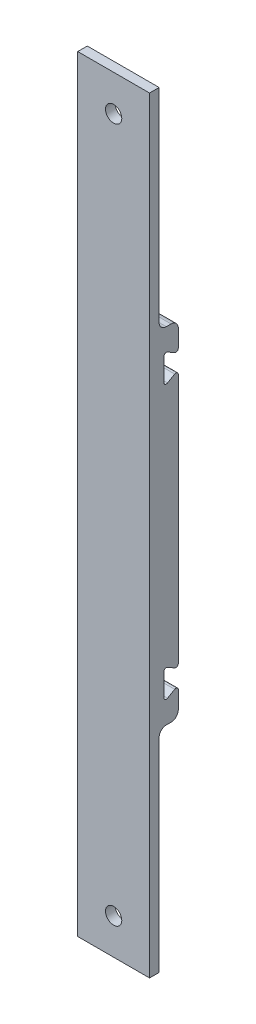
SolidWorks part; units mm, degrees
material "ABS"
ref_plane "Спереди" through (0, 0, 0) normal (0, 0, 1) x (1, 0, 0)
ref_plane "Сверху" through (0, 0, 0) normal (0, 1, 0) x (1, 0, 0)
ref_plane "Справа" through (0, 0, 0) normal (1, 0, 0) x (0, 0, -1)
sketch "Эскиз1" plane through (0, 0, 0) normal (0, 0, 1) x (1, 0, 0)
  line L1 (0, 160) -> (15, 160)
  line L2 (0, 160) -> (0, 0)
  line L3 (0, 0) -> (15, 0)
  line L4 (15, 160) -> (15, 0)
  dimension "D1" = 160
  dimension "D2" = 15
extrude "Бобышка-Вытянуть1" add sketch "Эскиз1" against normal blind 2
fillet "Скругление1" [suppressed] radius 6
sketch "Эскиз4" plane through (15, 0, 0) normal (1, 0, 0) x (0, 0, -1)
  line L0 (0, 160) -> (0, 0) construction
  line L1 (0, 116) -> (6, 116)
  line L2 (0, 116) -> (0, 101)
  line L3 (0, 101) -> (6, 101)
  line L4 (6, 116) -> (6, 101)
  line L6 (0, 59) -> (6, 59)
  line L7 (0, 59) -> (0, 44)
  line L8 (0, 44) -> (6, 44)
  line L9 (6, 59) -> (6, 44)
  dimension "D1" = 15
  dimension "D2" = 44
  dimension "D3" = 44
  dimension "D4" = 6
extrude "Бобышка-Вытянуть2" add sketch "Эскиз4" along direction (-1, 0, 0) on the side against the normal up to surface (15 mm away)
sketch "Эскиз3" plane through (15, 0, 0) normal (1, 0, 0) x (0, 0, -1)
  line L1 (2, 44) -> (6, 44) construction
  line L10 (6, 110) -> (3, 111.7321)
  line L11 (6, 101) -> (6, 116) construction
  line L12 (3, 111.7321) -> (3, 105.2679)
  line L13 (3, 105.2679) -> (6, 107)
  line L14 (6, 107) -> (6, 110)
  line L15 (6, 53) -> (3, 54.7321)
  line L16 (6, 44) -> (6, 59) construction
  line L17 (3, 54.7321) -> (3, 48.2679)
  line L18 (3, 48.2679) -> (6, 50)
  line L19 (6, 50) -> (6, 53)
  dimension "D1" = 3
  dimension "D2" = 60
  dimension "D3" = 3
  dimension "D4" = 6
  dimension "D5" = 6
fillet "Скругление3" radius 1.5 8 edges at (7.5, 59, -2) (7.5, 44, -2) (7.5, 44, -6) (7.5, 59, -6) (7.5, 101, -2) (7.5, 101, -6) (7.5, 116, -6) (7.5, 116, -2)
sketch "Эскиз5" plane through (0, 0, -2) normal (0, 0, -1) x (-1, 0, 0)
  line L0 (-15, 160) -> (0, 160) construction
  line L2 (0, 0) -> (-15, 0) construction
  line L3 (0, 160) -> (0, 117.5) construction
  point P0 (-7.5, 152.5)
  point P1 (-7.5, 7.5)
  dimension "D1" = 7.5
  dimension "D2" = 7.5
  dimension "D3" = 7.5
hole_wizard "Отверстие с зазором M31" positions "Эскиз6" profile "Эскиз7" hole size "M3" standard "DIN" end condition through all
sketch "Эскиз6" plane through (0, 0, -2) normal (0, 0, -1) x (-1, 0, 0)
  point P0 (-7.5, 152.5)
  point P3 (-7.5, 7.5)
sketch "Эскиз7" plane through (7.5, 152.5, -2) normal (1, 0, 0) x (0, 1, 0)
  line L0 (0, 0) -> (0, 2)
  line L1 (0, 2) -> (1.7, 2)
  line L2 (1.7, 2) -> (1.7, 0)
  line L5 (1.7, 0) -> (0, 0)
  line L11 (0, -6.35) -> (0, 107.95) construction
  dimension "Диаметр сквозного отверстия" = 3.4
  dimension "Глубина сквозного отверстия" = 2
extrude "Вырез-Вытянуть2" cut sketch "Эскиз3" against normal blind 13.5
fillet "Скругление4" radius 0.5 8 edges at (8.25, 107, -6) (8.25, 105.2679, -3) (8.25, 111.7321, -3) (8.25, 110, -6) (8.25, 48.2679, -3) (8.25, 54.7321, -3) (8.25, 50, -6) (8.25, 53, -6)
sketch "Эскиз8" plane through (15, 0, 0) normal (1, 0, 0) x (0, 0, -1)
  line L0 (0, 0) -> (0, 160) construction
  line L1 (6, 102.5) -> (0, 102.5)
  line L2 (6, 102.5) -> (6, 57.5)
  line L3 (6, 57.5) -> (0, 57.5)
  line L4 (0, 102.5) -> (0, 57.5)
  arc A0 (4.5, 101) -> (6, 102.5) centre (4.5, 102.5) ccw construction
  point P9 (0, 0)
extrude "Бобышка-Вытянуть3" add sketch "Эскиз8" against normal blind 15
